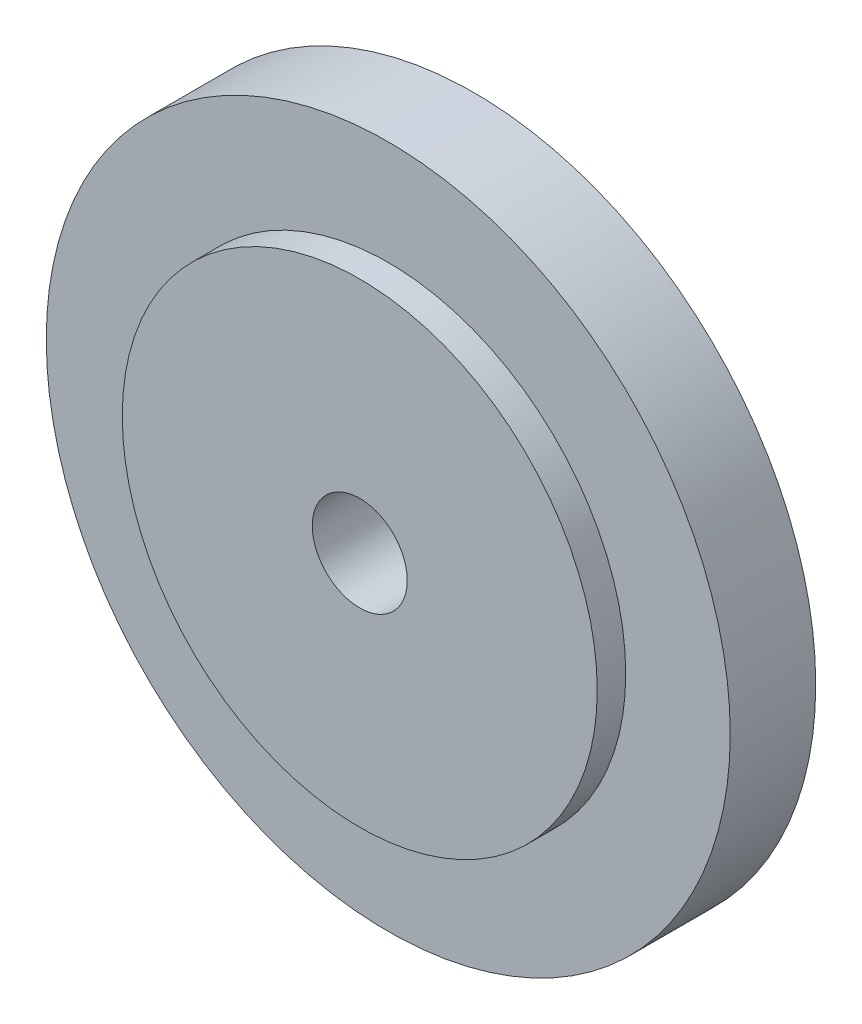
SolidWorks part; units mm, degrees
material "1060 Alloy"
ref_plane "Front Plane" through (0, 0, 0) normal (0, 0, 1) x (1, 0, 0)
ref_plane "Top Plane" through (0, 0, 0) normal (0, 1, 0) x (1, 0, 0)
ref_plane "Right Plane" through (0, 0, 0) normal (1, 0, 0) x (0, 0, -1)
sketch "Sketch1" plane through (0, 0, 0) normal (0, 0, 1) x (1, 0, 0)
  circle A0 centre (0, 0) radius 18
  dimension "D1" = 36
extrude "Boss-Extrude1" add sketch "Sketch1" along normal blind 4.5
sketch "Sketch2" plane through (0, 0, 4.5) normal (0, 0, 1) x (1, 0, 0)
  circle A0 centre (0, 0) radius 12.5
  dimension "D1" = 25
extrude "Boss-Extrude2" add sketch "Sketch2" along normal blind 1.5
sketch "Sketch3" plane through (0, 0, 6) normal (0, 0, 1) x (1, 0, 0)
  circle A0 centre (0, 0) radius 2.5
extrude "Cut-Extrude1" cut sketch "Sketch3" against normal through all
